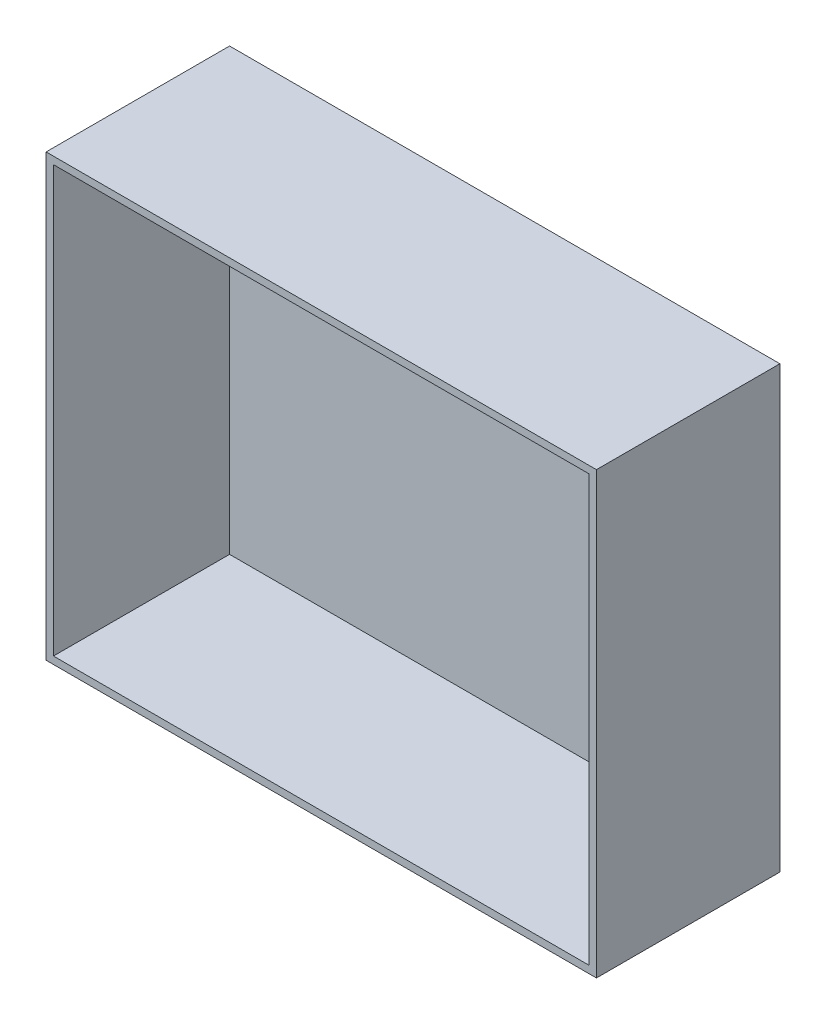
SolidWorks part; units mm, degrees
ref_plane "Front Plane" through (0, 0, 0) normal (0, 0, 1) x (1, 0, 0)
ref_plane "Top Plane" through (0, 0, 0) normal (0, 1, 0) x (1, 0, 0)
ref_plane "Right Plane" through (0, 0, 0) normal (1, 0, 0) x (0, 0, -1)
sketch "Sketch1" plane through (0, 0, 0) normal (0, 0, 1) x (1, 0, 0)
  line L1 (-75, 60) -> (75, 60)
  line L2 (-75, 60) -> (-75, -60)
  line L3 (-75, -60) -> (75, -60)
  line L4 (75, 60) -> (75, -60)
  line L5 (-75, 60) -> (75, -60) construction
  line L6 (-75, -60) -> (75, 60) construction
  point P0 (0, 0)
  dimension "D1" = 150
  dimension "D2" = 120
extrude "Boss-Extrude1" add sketch "Sketch1" along normal mid plane 50
shell "Shell1" thickness 2
